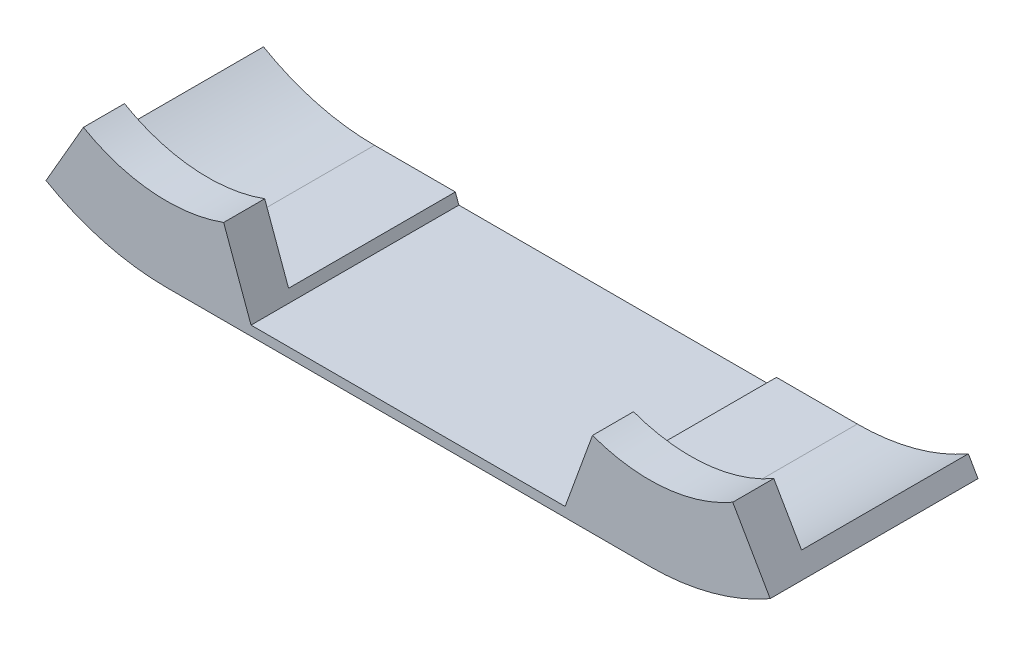
SolidWorks part; units mm, degrees
ref_plane "前视基准面" through (0, 0, 0) normal (0, 0, 1) x (1, 0, 0)
ref_plane "上视基准面" through (0, 0, 0) normal (0, 1, 0) x (1, 0, 0)
ref_plane "右视基准面" through (0, 0, 0) normal (1, 0, 0) x (0, 0, -1)
sketch "草图1" plane through (0, 0, 0) normal (0, 0, 1) x (1, 0, 0)
  line L4 (0, -50) -> (25, -50)
  line L15 (-25, -43.3013) -> (-17.25, -29.8779)
  line L18 (11.7997, -32.4194) -> (17.4706, -48)
  line L19 (17.4706, -48) -> (25, -48)
  line L21 (75, -48) -> (25, -48)
  line L22 (25, -50) -> (75, -50)
  line L23 (82.5294, -48) -> (75, -48)
  line L24 (88.2003, -32.4194) -> (82.5294, -48)
  line L25 (125, -43.3013) -> (117.25, -29.8779)
  line L26 (100, -50) -> (75, -50)
  arc A2 (0, -34.5) -> (-17.25, -29.8779) centre (0, 0) cw
  arc A3 (0, -34.5) -> (11.7997, -32.4194) centre (0, 0) ccw
  arc A6 (0, -50) -> (-25, -43.3013) centre (0, 0) cw
  arc A7 (100, -50) -> (125, -43.3013) centre (100, 0) ccw
  arc A8 (100, -34.5) -> (88.2003, -32.4194) centre (100, 0) cw
  arc A9 (100, -34.5) -> (117.25, -29.8779) centre (100, 0) ccw
  point P20 (50, -50)
extrude "凸台-拉伸1" add sketch "草图1" along normal blind 8.5
sketch "草图3" plane through (0, 0, 0) normal (0, 0, 1) x (1, 0, 0)
  line L14 (-23, -39.8372) -> (-25, -43.3013)
  line L15 (0, -50) -> (100, -50) construction
  line L18 (0, -46) -> (16.7426, -46)
  line L19 (17.4706, -48) -> (11.7997, -32.4194) construction
  line L22 (0, -50) -> (100, -50)
  line L24 (16.7426, -46) -> (17.4706, -48)
  line L25 (83.2574, -46) -> (82.5294, -48)
  line L26 (100, -46) -> (83.2574, -46)
  line L27 (123, -39.8372) -> (125, -43.3013)
  line L28 (17.4706, -48) -> (82.5294, -48)
  arc A3 (-25, -43.3013) -> (0, -50) centre (0, 0) ccw
  arc A6 (0, -46) -> (-23, -39.8372) centre (0, 0) cw
  arc A7 (100, -46) -> (123, -39.8372) centre (100, 0) ccw
  arc A8 (125, -43.3013) -> (100, -50) centre (100, 0) cw
extrude "凸台-拉伸5" add sketch "草图3" against normal blind 34.55
